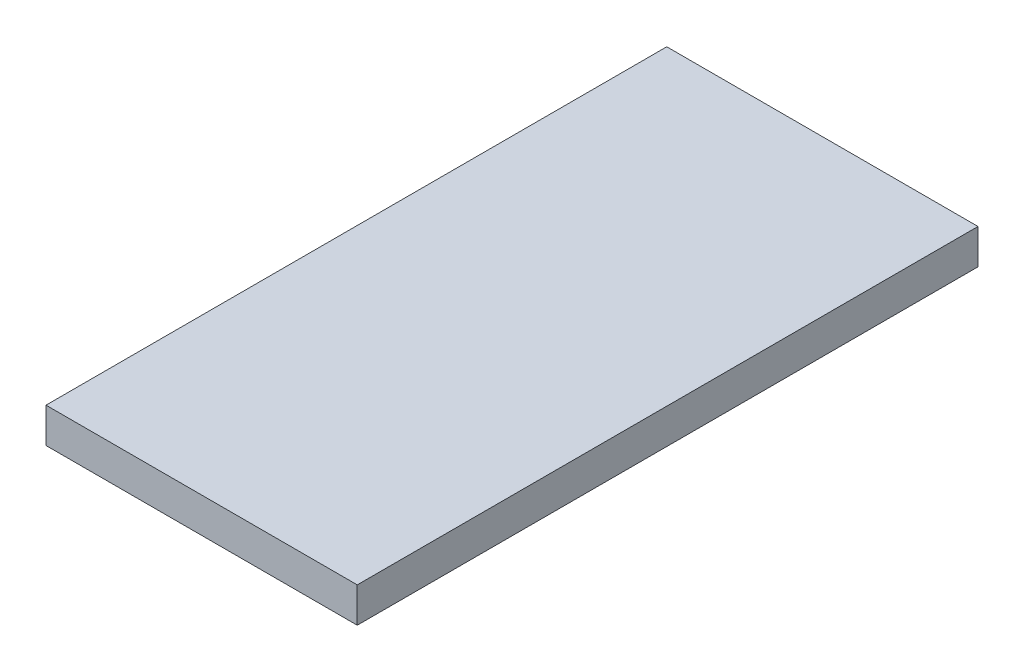
SolidWorks part; units mm, degrees
ref_plane "Front Plane" through (0, 0, 0) normal (0, 0, 1) x (1, 0, 0)
ref_plane "Top Plane" through (0, 0, 0) normal (0, 1, 0) x (1, 0, 0)
ref_plane "Right Plane" through (0, 0, 0) normal (1, 0, 0) x (0, 0, -1)
sketch "Sketch1" plane through (0, 0, 0) normal (0, 1, 0) x (1, 0, 0)
  line L1 (-8.9, 17.75) -> (8.9, 17.75)
  line L2 (-8.9, 17.75) -> (-8.9, -17.75)
  line L3 (-8.9, -17.75) -> (8.9, -17.75)
  line L4 (8.9, 17.75) -> (8.9, -17.75)
  line L5 (-8.9, 17.75) -> (8.9, -17.75) construction
  line L6 (-8.9, -17.75) -> (8.9, 17.75) construction
  point P1 (0, 0)
  dimension "D1" = 17.8
  dimension "D2" = 35.5
extrude "Boss-Extrude1" add sketch "Sketch1" along normal blind 2
